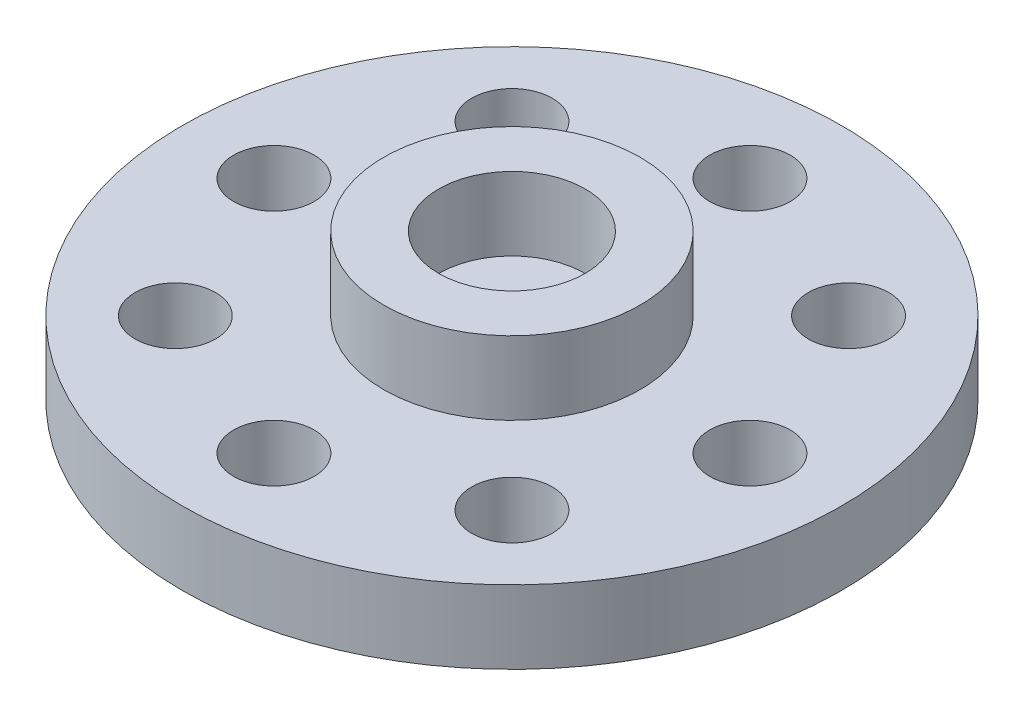
SolidWorks part; units mm, degrees
ref_plane "前视基准面" through (0, 0, 0) normal (0, 0, 1) x (1, 0, 0)
ref_plane "上视基准面" through (0, 0, 0) normal (0, 1, 0) x (1, 0, 0)
ref_plane "右视基准面" through (0, 0, 0) normal (1, 0, 0) x (0, 0, -1)
other "Configuration Table"
sketch "草图1" plane through (0, 0, 0) normal (0, 1, 0) x (1, 0, 0)
  circle A0 centre (0, 0) radius 9
  dimension "D1" = 18
extrude "凸台-拉伸1" add sketch "草图1" along normal blind 2
sketch "草图2" plane through (0, 2, 0) normal (0, 1, 0) x (1, 0, 0)
  circle A0 centre (0, 0) radius 2
  circle A1 centre (0, 0) radius 3.5
  dimension "D1" = 7
  dimension "D2" = 4
extrude "凸台-拉伸2" add sketch "草图2" along normal blind 2
sketch "草图3" plane through (0, 0, 0) normal (0, -1, 0) x (1, 0, 0)
  circle A0 centre (0, 6.5) radius 1.1
  circle A1 centre (4.5962, 4.5962) radius 1.1
  circle A2 centre (6.5, 0) radius 1.1
  circle A3 centre (4.5962, -4.5962) radius 1.1
  circle A4 centre (0, -6.5) radius 1.1
  circle A5 centre (-4.5962, -4.5962) radius 1.1
  circle A6 centre (-6.5, 0) radius 1.1
  circle A7 centre (-4.5962, 4.5962) radius 1.1
  point P3 (0, 0)
  point P4 (9, -6.0766)
  point P18 (0, 0)
  point P19 (0, 0)
  dimension "D1" = 2.2
  dimension "D3" = 13
  dimension "D2" = 8
extrude "切除-拉伸1" cut sketch "草图3" against normal through all
